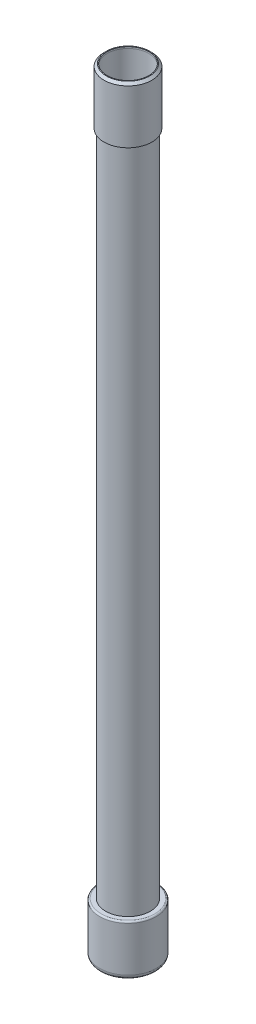
SolidWorks part; units mm, degrees
ref_plane "Front Plane" through (0, 0, 0) normal (0, 0, 1) x (1, 0, 0)
ref_plane "Top Plane" through (0, 0, 0) normal (0, 1, 0) x (1, 0, 0)
ref_plane "Right Plane" through (0, 0, 0) normal (1, 0, 0) x (0, 0, -1)
sketch "Sketch1" plane through (0, 0, 0) normal (0, 1, 0) x (1, 0, 0)
  circle A0 centre (0, 0) radius 14
  circle A1 centre (0, 0) radius 13
  dimension "D1" = 28
  dimension "D2" = 1
extrude "Extrude1" add sketch "Sketch1" along normal mid plane 480
sketch "Sketch2" plane through (0, 0, 0) normal (0, 0, 1) x (1, 0, 0)
  line L0 (0, -191.8545) -> (0, -266.8259) construction
  line L1 (13, -211) -> (17.75, -211)
  line L2 (17.75, -211) -> (17.75, -242)
  line L3 (-14, -240) -> (14, -240) construction
  line L4 (0, -246) -> (-44.4365, -246) construction
  line L6 (13, -240) -> (13, 240) construction
  line L7 (13, -240) -> (13, -211)
  line L8 (-13, -240) -> (13, -240) construction
  line L9 (0, -240) -> (13, -240)
  line L10 (0, -240) -> (0, -246)
  arc A0 (0, -246) -> (17.75, -242) centre (0, -204.6172) ccw
  dimension "D1" = 35.5
  dimension "D2" = 6
  dimension "D3" = 2
  dimension "D4" = 35
revolve "Revolve1" add sketch "Sketch2" angle 360 about L0
fillet "Fillet1" radius 3 1 edges at (0, -242, 17.75)
fillet "Fillet2" radius 1 1 edges at (0, -211, 17.75)
sketch "Sketch3" plane through (0, 0, 0) normal (0, 0, 1) x (1, 0, 0)
  line L0 (0, 250.6488) -> (0, 200.6455) construction
  line L1 (15, 241) -> (15, 206)
  line L2 (14, -240) -> (14, 240) construction
  line L3 (14, 206) -> (14, 240)
  line L4 (15, 206) -> (14, 206)
  line L5 (13, 241) -> (15, 241)
  line L6 (13, 240) -> (-13, 240) construction
  line L7 (13, -240) -> (13, 240) construction
  line L8 (13, 240) -> (13, 241)
  line L9 (14, 240) -> (-14, 240) construction
  line L10 (14, 240) -> (13, 240)
  dimension "D1" = 30
  dimension "D2" = 35
  dimension "D3" = 1
revolve "Revolve2" add sketch "Sketch3" angle 360 about L0
chamfer "Chamfer1" distance 1.5 angle 45 1 edges at (0, 241, 15)
sketch "Sketch4" plane through (0, 0, 0) normal (0, 0, 1) x (1, 0, 0)
  arc A0 (-15.9029, -242.8224) -> (15.9029, -242.8224) centre (0, -204.6172) ccw construction
  point P0 (0, -246)
  dimension "D6" = 1
